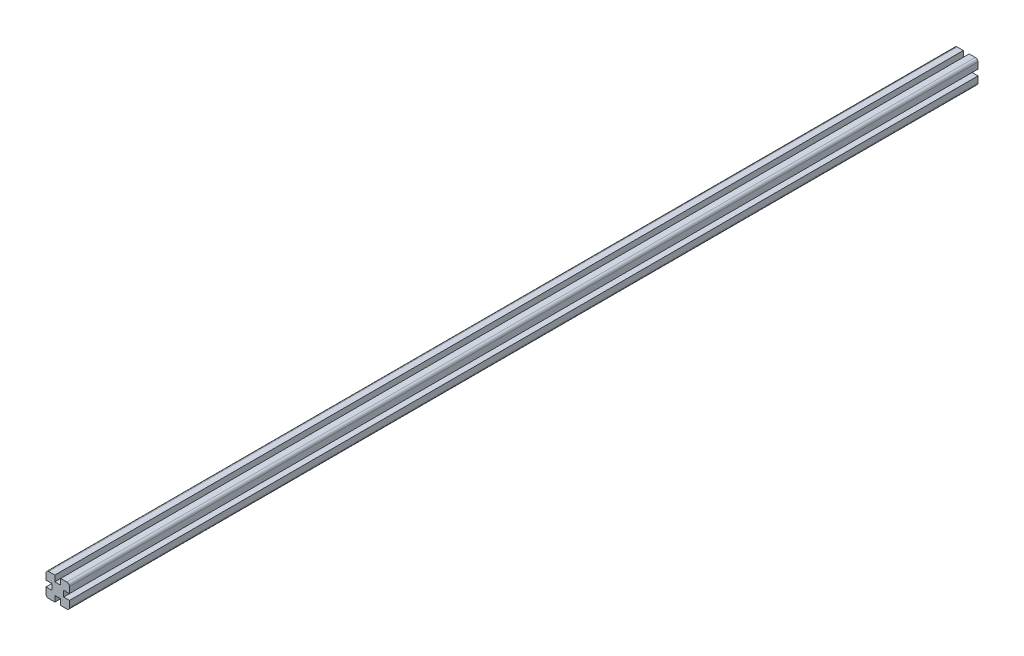
SolidWorks part; units mm, degrees
ref_plane "Front Plane" through (0, 0, 0) normal (0, 0, 1) x (1, 0, 0)
ref_plane "Top Plane" through (0, 0, 0) normal (0, 1, 0) x (1, 0, 0)
ref_plane "Right Plane" through (0, 0, 0) normal (1, 0, 0) x (0, 0, -1)
sketch "Sketch1" plane through (0, 0, 0) normal (0, 0, 1) x (1, 0, 0)
  line L0 (0, 0) -> (0, -50000) construction
  line L1 (-15.5, -20) -> (-5, -20)
  line L2 (-20, -15.5) -> (-20, -5)
  line L3 (-15.5, 20) -> (-15, 20)
  line L4 (20, -15.5) -> (20, -5)
  line L5 (-20, -20) -> (20, 20) construction
  line L6 (-20, 20) -> (20, -20) construction
  line L8 (-5, -20) -> (-5, -10)
  line L9 (-5, -10) -> (5, -10)
  line L10 (5, -20) -> (5, -10)
  line L15 (5, -20) -> (15.5, -20)
  line L16 (-8, 20) -> (-5, 20)
  line L18 (-15, 20) -> (-8, 20)
  line L19 (-20, 5) -> (-10, 5)
  line L20 (-10, 5) -> (-10, -5)
  line L21 (-20, -5) -> (-10, -5)
  line L22 (5, 20) -> (5, 10)
  line L23 (5, 10) -> (-5, 10)
  line L24 (-5, 20) -> (-5, 10)
  line L25 (20, -5) -> (10, -5)
  line L26 (10, -5) -> (10, 5)
  line L27 (20, 5) -> (10, 5)
  line L28 (-20, 5) -> (-20, 15.5)
  line L29 (5, 20) -> (15.5, 20)
  line L30 (20, 5) -> (20, 15.5)
  arc A0 (-20, 15.5) -> (-15.5, 20) centre (-15.5, 15.5) cw
  arc A1 (-15.5, -20) -> (-20, -15.5) centre (-15.5, -15.5) cw
  arc A2 (15.5, -20) -> (20, -15.5) centre (15.5, -15.5) ccw
  arc A3 (15.5, 20) -> (20, 15.5) centre (15.5, 15.5) cw
  point P0 (0, 0)
  point P41 (0, 0)
  dimension "D8" = 4.5
  dimension "D1" = 40
  dimension "D2" = 40
  dimension "D3" = 15
  dimension "D4" = 10
  dimension "D5" = 5
  dimension "D6" = 28
  dimension "D7" = 4
extrude "Boss-Extrude1" add sketch "Sketch1" along normal blind 1550
